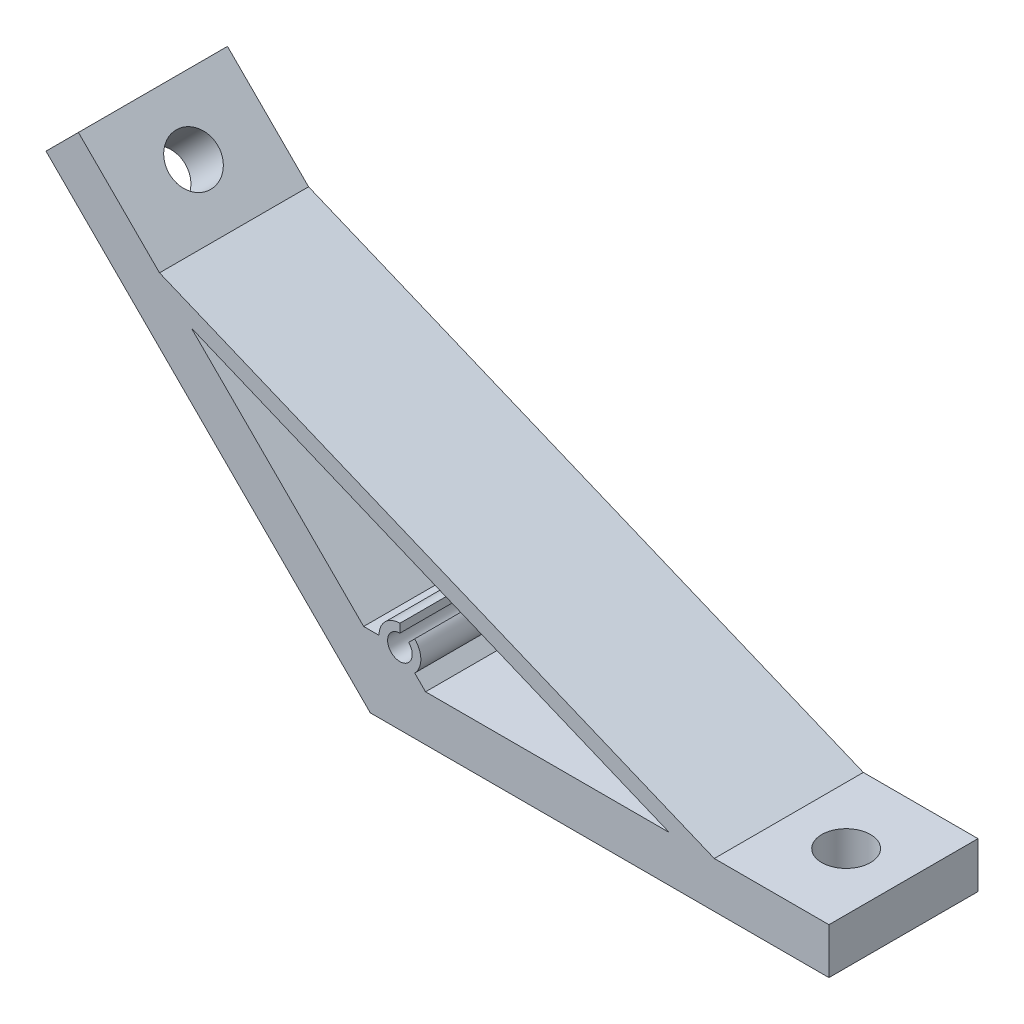
SolidWorks part; units mm, degrees
ref_plane "前视基准面" through (0, 0, 0) normal (0, 0, 1) x (1, 0, 0)
ref_plane "上视基准面" through (0, 0, 0) normal (0, 1, 0) x (1, 0, 0)
ref_plane "右视基准面" through (0, 0, 0) normal (1, 0, 0) x (0, 0, -1)
sketch "草图1" plane through (0, 0, 0) normal (0, 0, 1) x (1, 0, 0)
  line B0 (80, 0) -> (0, 0)
  line B1 (80, 8) -> (60, 8)
  line B2 (52.1606, 8) -> (9.6386, 8)
  line B3 (0, 0) -> (-56.5685, 56.5685)
  line B4 (-1.1587, 12.4724) -> (-31.2263, 42.54)
  line B5 (-36.7696, 48.0833) -> (-50.9117, 62.2254)
  line B6 (-50.9117, 62.2254) -> (-56.5685, 56.5685)
  line B7 (80, 8) -> (80, 0)
  line B8 (-1.1587, 12.4724) -> (1.5162, 12.4724)
  line B9 (9.6386, 8) -> (7.7472, 9.8914)
  line B10 (6.6865, 13.9927) -> (7.7472, 15.0533)
  line B11 (5.1662, 14.6224) -> (5.1662, 16.1224)
  line B12 (-36.7696, 48.0833) -> (60, 8)
  line B13 (-31.2263, 42.54) -> (52.1606, 8)
  arc B14 (5.1662, 14.6224) -> (6.6865, 13.9927) centre (5.1662, 12.4724) ccw
  arc B15 (7.7472, 9.8914) -> (7.7472, 15.0533) centre (5.1662, 12.4724) ccw
  arc B16 (5.1662, 16.1224) -> (1.5162, 12.4724) centre (5.1662, 12.4724) ccw
sketch_block_instance "A$C053212F5-1"
sketch_block "A$C053212F5"
extrude "凸台-拉伸1" add sketch "草图1" along normal mid plane 26
sketch "草图3" plane through (0, 8, 0) normal (0, 1, 0) x (1, 0, 0)
  line L0 (80, -13) -> (80, 13) construction
  circle A0 centre (70, 0) radius 4.25
  dimension "D1" = 10
extrude "切除-拉伸1" cut sketch "草图3" against normal through all
sketch "草图4" plane through (11.6152, 28.0416, 0) normal (0.3827, 0.9239, 0) x (0.9239, -0.3827, 0)
  line L0 (0, -13) -> (0, 13) construction
  line L1 (52.3713, -13) -> (-52.3713, -13) construction
  line L2 (52.3713, 13) -> (-52.3713, 13) construction
ref_plane "基准面2" through (0, 0, 0) normal (-0.9239, 0.3827, 0) x (0, 0, 1)
mirror "镜向1" about plane through (0, 0, 0) normal (-0.9239, 0.3827, 0) of "切除-拉伸1"
